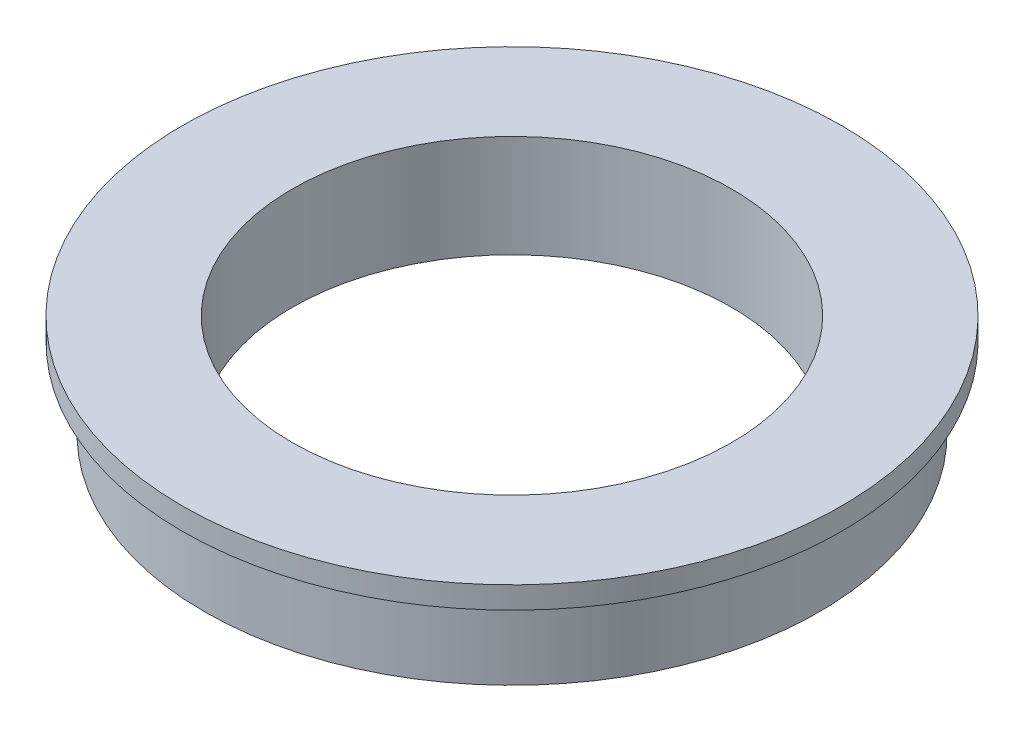
SolidWorks part; units mm, degrees
material "铸造不锈钢"
ref_plane "前视基准面" through (0, 0, 0) normal (0, 0, 1) x (1, 0, 0)
ref_plane "上视基准面" through (0, 0, 0) normal (0, 1, 0) x (1, 0, 0)
ref_plane "右视基准面" through (0, 0, 0) normal (1, 0, 0) x (0, 0, -1)
other "Configuration Table"
sketch "草图1" plane through (0, 0, 0) normal (0, 1, 0) x (1, 0, 0)
  circle A0 centre (0, 0) radius 15
  circle A1 centre (0, 0) radius 21
  dimension "D1" = 42
  dimension "D2" = 30
extrude "凸台-拉伸1" add sketch "草图1" along normal blind 5.5
sketch "草图2" plane through (0, 5.5, 0) normal (0, 1, 0) x (1, 0, 0)
  circle A0 centre (0, 0) radius 15
  circle A1 centre (0, 0) radius 22.5
  circle A2 centre (0, 0) radius 15 construction
  dimension "D2" = 45
extrude "凸台-拉伸2" add sketch "草图2" along normal blind 1.5
